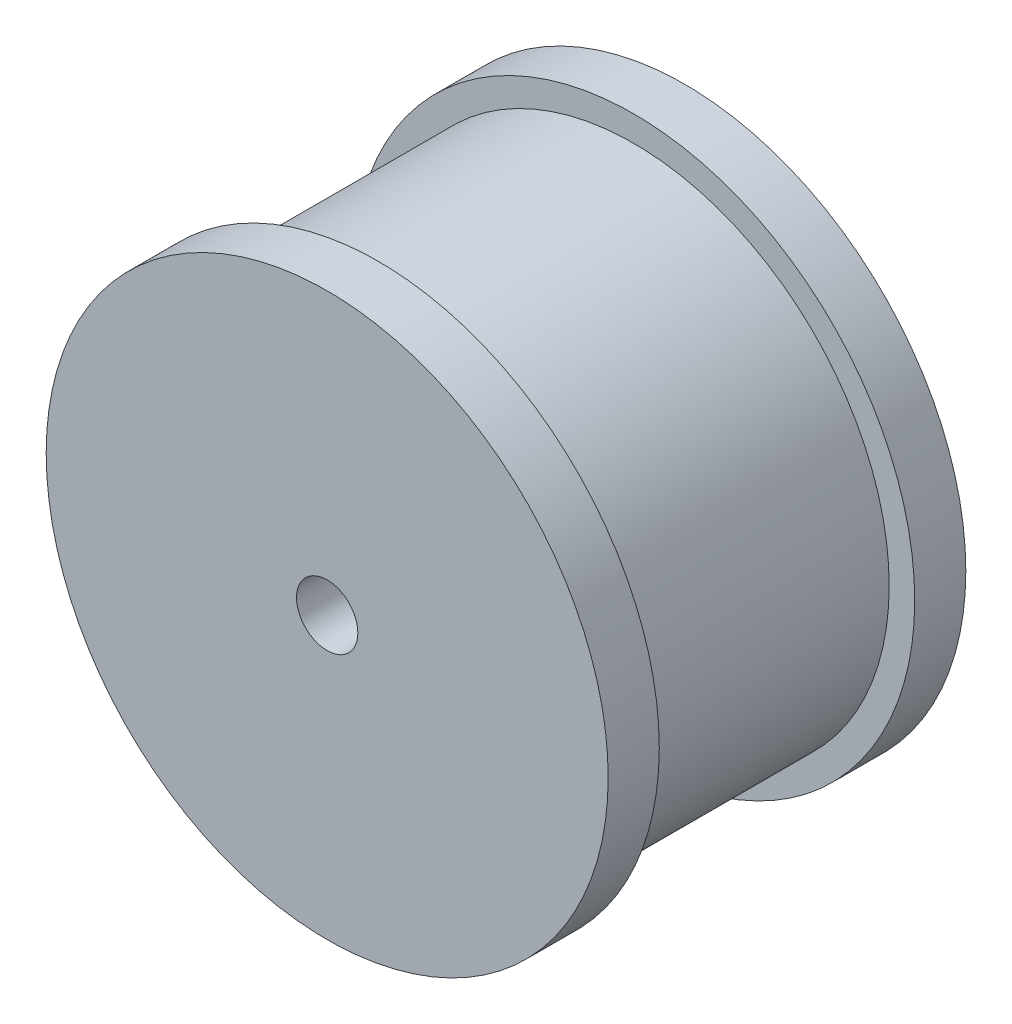
SolidWorks part; units mm, degrees
material "Alloy Steel"
ref_plane "Front Plane" through (0, 0, 0) normal (0, 0, 1) x (1, 0, 0)
ref_plane "Top Plane" through (0, 0, 0) normal (0, 1, 0) x (1, 0, 0)
ref_plane "Right Plane" through (0, 0, 0) normal (1, 0, 0) x (0, 0, -1)
sketch "Sketch1" plane through (0, 0, 0) normal (0, 0, 1) x (1, 0, 0)
  circle A0 centre (0, 0) radius 25
  circle A1 centre (0, 0) radius 3
  dimension "D1" = 50
  dimension "D2" = 6
extrude "Boss-Extrude1" add sketch "Sketch1" along normal blind 25
sketch "Sketch2" plane through (0, 0, 25) normal (0, 0, 1) x (1, 0, 0)
  circle A0 centre (0, 0) radius 27.5
  circle A1 centre (0, 0) radius 3 construction
  circle A2 centre (0, 0) radius 3
  dimension "D1" = 55
extrude "Boss-Extrude2" add sketch "Sketch2" along normal blind 5
sketch "Sketch3" plane through (0, 0, 0) normal (0, 0, -1) x (-1, 0, 0)
  circle A0 centre (0, 0) radius 3 construction
  circle A1 centre (0, 0) radius 27.5 construction
  circle A2 centre (0, 0) radius 3
  circle A3 centre (0, 0) radius 27.5
extrude "Boss-Extrude3" add sketch "Sketch3" along normal blind 5
